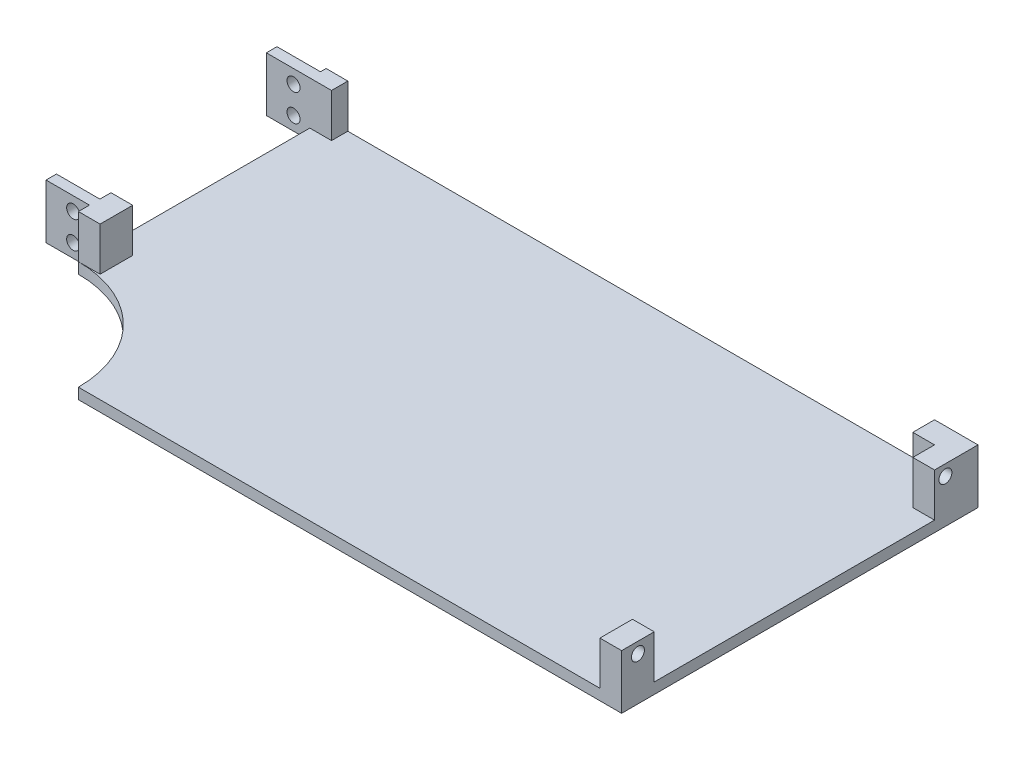
SolidWorks part; units mm, degrees
ref_plane "Front Plane" through (0, 0, 0) normal (0, 0, 1) x (1, 0, 0)
ref_plane "Top Plane" through (0, 0, 0) normal (0, 1, 0) x (1, 0, 0)
ref_plane "Right Plane" through (0, 0, 0) normal (1, 0, 0) x (0, 0, -1)
sketch "Sketch1" plane through (0, 0, 0) normal (0, 1, 0) x (1, 0, 0)
  line L0 (-75, 0) -> (75, 0)
  line L1 (75, 0) -> (75, -82)
  line L2 (-75, 0) -> (-75, -57)
  line L3 (-50, -82) -> (75, -82)
  arc A1 (-75, -57) -> (-50, -82) centre (-75, -82) cw
  point P3 (0, 0)
  point P4 (0, 0)
  dimension "D3" = 25
  dimension "D1" = 150
  dimension "D2" = 57
extrude "Boss-Extrude1" add sketch "Sketch1" along normal blind 2.5
sketch "Sketch2" plane through (0, 2.5, 0) normal (0, 1, 0) x (1, 0, 0)
  line L1 (-75, 0) -> (-70, 0)
  line L2 (-75, 0) -> (-75, -3.75)
  line L3 (-75, -3.75) -> (-70, -3.75)
  line L4 (-70, 0) -> (-70, -3.75)
  line L5 (-75, -57) -> (-70, -57)
  line L6 (-75, -57) -> (-75, -49.5)
  line L7 (-75, -49.5) -> (-70, -49.5)
  line L8 (-70, -57) -> (-70, -49.5)
  dimension "D1" = 5
  dimension "D2" = 7.5
  dimension "D3" = 3.75
extrude "Boss-Extrude2" add sketch "Sketch2" along normal blind 10
sketch "Sketch4" plane through (-75, 0, 0) normal (-1, 0, 0) x (0, 0, 1)
  line L0 (49.5, 12.5) -> (57, 12.5) construction
  line L1 (54.45, 12.5) -> (52.05, 12.5)
  line L2 (54.45, 12.5) -> (54.45, 0)
  line L3 (54.45, 0) -> (52.05, 0)
  line L4 (52.05, 12.5) -> (52.05, 0)
  line L5 (0, 0) -> (57, 0) construction
  line L6 (57, 12.5) -> (57, 2.5) construction
  line L7 (3.75, 12.5) -> (1.3, 12.5)
  line L8 (3.75, 12.5) -> (3.75, 0)
  line L9 (3.75, 0) -> (1.3, 0)
  line L10 (1.3, 12.5) -> (1.3, 0)
  line L11 (49.5, 12.5) -> (49.5, 2.5) construction
  dimension "D1" = 2.55
  dimension "D2" = 2.55
  dimension "D3" = 2.45
extrude "Boss-Extrude3" add sketch "Sketch4" along normal blind 10
sketch "Sketch5" plane through (0, 0, 1.3) normal (0, 0, -1) x (-1, 0, 0)
  circle A0 centre (78.75, 9.375) radius 1.5
  circle A1 centre (78.75, 3.125) radius 1.5
  dimension "D1" = 3
  dimension "D2" = 3
extrude "Cut-Extrude1" cut sketch "Sketch5" against normal blind 57
sketch "Sketch6" plane through (0, 2.5, 0) normal (0, 1, 0) x (1, 0, 0)
  line L0 (75, 0) -> (65, 0)
  line L5 (75, -82) -> (70, -82)
  line L6 (75, -82) -> (75, -74.5)
  line L7 (75, -74.5) -> (70, -74.5)
  line L8 (70, -82) -> (70, -74.5)
  line L9 (75, 0) -> (-70, 0) construction
  line L10 (65, 0) -> (65, -5)
  line L11 (65, -5) -> (70, -5)
  line L12 (70, -5) -> (70, -10)
  line L13 (70, -10) -> (75, -10)
  line L14 (75, -82) -> (75, 0) construction
  line L15 (75, -10) -> (75, 0)
  dimension "D1" = 10
  dimension "D2" = 7.5
  dimension "D3" = 5
  dimension "D4" = 5
extrude "Boss-Extrude4" add sketch "Sketch6" along normal blind 10
sketch "Sketch8" plane through (70, 0, 0) normal (-1, 0, 0) x (0, 0, 1)
  line L0 (5, 12.5) -> (10, 12.5) construction
  line L1 (10, 7.5) -> (5, 7.5) construction
  line L2 (10, 12.5) -> (10, 2.5) construction
  line L3 (5, 12.5) -> (5, 2.5) construction
  line L4 (7.5, 7.5) -> (7.5, 12.5) construction
  circle A0 centre (7.5, 10) radius 1.5
  point P4 (7.5, 12.5)
  point P13 (7.5, 10)
  dimension "D1" = 3
extrude "Cut-Extrude2" cut sketch "Sketch8" against normal blind 5
sketch "Sketch9" plane through (0, 0, 5) normal (0, 0, 1) x (1, 0, 0)
  line L0 (70, 7.5) -> (65, 7.5) construction
  line L1 (70, 12.5) -> (70, 2.5) construction
  line L2 (65, 12.5) -> (65, 2.5) construction
  line L3 (67.5, 7.5) -> (67.5, 2.5) construction
  line L4 (65, 2.5) -> (70, 2.5) construction
  circle A0 centre (67.5, 5) radius 1.5
  point P12 (0, 0)
  point P13 (67.5, 5)
  dimension "D1" = 3
extrude "Cut-Extrude3" cut sketch "Sketch9" against normal blind 5
sketch "Sketch10" plane through (70, 0, 0) normal (-1, 0, 0) x (0, 0, 1)
  line L0 (82, 7.5) -> (74.5, 7.5) construction
  line L1 (82, 12.5) -> (82, 2.5) construction
  line L2 (74.5, 12.5) -> (74.5, 2.5) construction
  line L3 (78.25, 12.5) -> (78.25, 7.5) construction
  line L4 (74.5, 12.5) -> (82, 12.5) construction
  circle A0 centre (78.25, 10) radius 1.5
  dimension "D1" = 3
extrude "Cut-Extrude4" cut sketch "Sketch10" against normal blind 5
